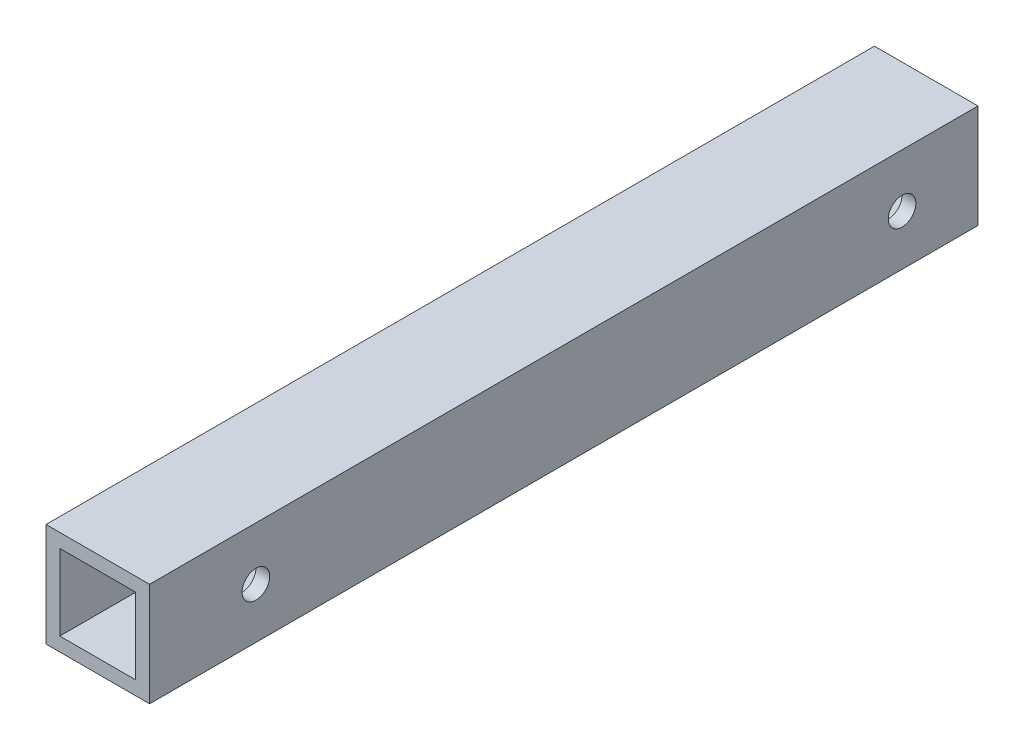
SolidWorks part; units mm, degrees
ref_plane "Front Plane" through (0, 0, 0) normal (0, 0, 1) x (1, 0, 0)
ref_plane "Top Plane" through (0, 0, 0) normal (0, 1, 0) x (1, 0, 0)
ref_plane "Right Plane" through (0, 0, 0) normal (1, 0, 0) x (0, 0, -1)
sketch "Sketch1" plane through (0, 0, 0) normal (0, 0, 1) x (1, 0, 0)
  line L0 (5.5, 5.5) -> (-5.5, 5.5)
  line L1 (7.5, -7.5) -> (-7.5, -7.5)
  line L2 (7.5, -7.5) -> (7.5, 7.5)
  line L3 (7.5, 7.5) -> (-7.5, 7.5)
  line L4 (-7.5, -7.5) -> (-7.5, 7.5)
  line L5 (7.5, -7.5) -> (-7.5, 7.5) construction
  line L6 (7.5, 7.5) -> (-7.5, -7.5) construction
  line L7 (-5.5, -5.5) -> (-5.5, 5.5)
  line L8 (5.5, -5.5) -> (-5.5, -5.5)
  line L9 (5.5, -5.5) -> (5.5, 5.5)
  point P0 (0, 0)
  dimension "D1" = 15
  dimension "D2" = 2
extrude "Boss-Extrude1" add sketch "Sketch1" along normal mid plane 120
sketch "Sketch2" plane through (7.5, 0, 0) normal (1, 0, 0) x (0, 0, -1)
  circle A0 centre (-44.5991, -0.2) radius 2
  circle A1 centre (49, -0.2) radius 2
  dimension "D1" = 4
extrude "Cut-Extrude1" cut sketch "Sketch2" against normal through all both and the other way through all
